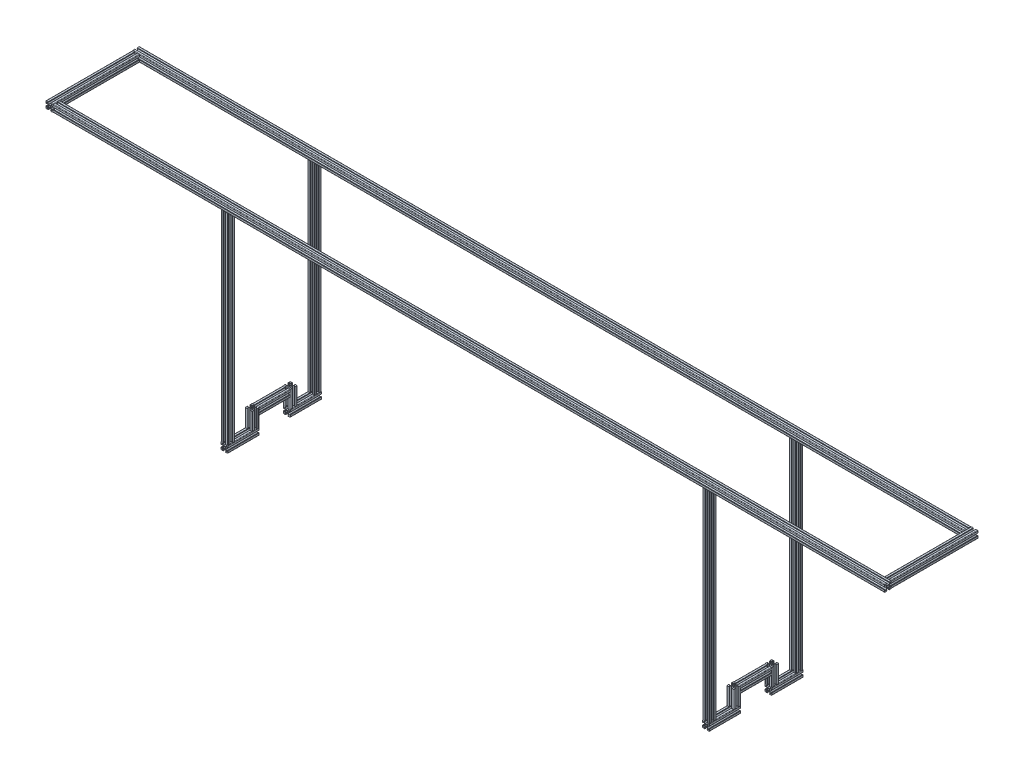
SolidWorks part; units mm, degrees
ref_plane "前视基准面" through (0, 0, 0) normal (0, 0, 1) x (1, 0, 0)
ref_plane "上视基准面" through (0, 0, 0) normal (0, 1, 0) x (1, 0, 0)
ref_plane "右视基准面" through (0, 0, 0) normal (1, 0, 0) x (0, 0, -1)
sketch "草图3" plane through (0, 0, 0) normal (0, 1, 0) x (1, 0, 0)
  line L0 (0, 0) -> (0, 250)
  line L1 (0, 250) -> (2400, 250)
  line L2 (2400, 250) -> (2400, 0)
  line L3 (2400, 0) -> (0, 0)
  dimension "D1" = 2400
  dimension "D2" = 250
sketch3d "3D草图2"
  line L0 (1200, 600, 0) -> (1200, -51.0391, 0) construction
  line L1 (2400, 0, -250) -> (2400, 0, 0) construction
  line L2 (505, 600, 0) -> (505, 0, 0)
  line L3 (0, 0, 0) -> (0, 0, -250) construction
  line L5 (2400, 0, -250) -> (2400, 0, 0) construction
  line L7 (0, 0, 0) -> (0, 0, -250) construction
  line L9 (0, 600, 0) -> (0, 600, -250)
  line L10 (0, 600, -250) -> (0, 0, -250) construction
  line L11 (0, 600, 0) -> (2400, 600, 0)
  line L12 (2400, 600, 0) -> (2400, 0, 0) construction
  line L13 (2400, 600, 0) -> (2400, 600, -250)
  line L14 (2400, 600, -250) -> (2400, 0, -250) construction
  line L15 (0, 600, -250) -> (2400, 600, -250)
  line L16 (1895, 600, 0) -> (1895, 0, 0)
  line L17 (1895, 600, -250) -> (1895, 0, -250)
  line L18 (505, 600, -250) -> (505, 0, -250)
  line L19 (1200, 600, -250) -> (1200, -43.6003, -250) construction
  line L20 (505, 0, 0) -> (505, 0, -70)
  line L21 (1895, 0, 0) -> (1895, 0, -70)
  line L22 (505, 0, -180) -> (505, 50, -180)
  line L23 (505, 50, -180) -> (505, 50, -70)
  line L24 (505, 50, -70) -> (505, 0, -70)
  line L25 (505, 0, -180) -> (505, 0, -250)
  line L26 (1895, 0, -70) -> (1895, 50, -70)
  line L27 (1895, 50, -70) -> (1895, 50, -180)
  line L28 (1895, 50, -180) -> (1895, 0, -180)
  line L29 (1895, 0, -180) -> (1895, 0, -250)
  dimension "D1" = 600
  dimension "D2" = 600
  dimension "D7" = 600
  dimension "D3" = 695
  dimension "D4" = 600
  dimension "D5" = 695
  dimension "D6" = 695
  dimension "D8" = 695
  dimension "D9" = 600
  dimension "D10" = 110
  dimension "D11" = 50
  dimension "D12" = 70
  dimension "D13" = 70
  dimension "D14" = 110
  dimension "D15" = 50
  dimension "D16" = 70
  dimension "D17" = 70
other "工业铝型材 20 X 20 X R1.5(1)"
ref_plane "基准面2" through (0, 600, 0) normal (0, 0, -1) x (1, 0, 0)
sketch "Sketch14" plane through (0, 600, 0) normal (0, 0, -1) x (1, 0, 0)
  line L0 (-3.6, 10) -> (-3.6, 9.5)
  line L1 (-3.6, 9.5) -> (-3.1, 9.5)
  line L2 (-3.1, 9.5) -> (-3.1, 8.5)
  line L3 (-3.1, 8.5) -> (-5.5, 8.5)
  line L4 (-8.5, -10) -> (-3.6, -10)
  line L5 (-10, -8.5) -> (-10, -3.6)
  line L6 (8.5, 10) -> (3.6, 10)
  line L7 (10, 8.5) -> (10, 3.6)
  line L8 (0, 14.8756) -> (0, 0) construction
  line L9 (0, 0) -> (14.1675, 0) construction
  line L10 (-5.5, 8.5) -> (-5.5, 6.65)
  line L11 (-5.5, 6.65) -> (-2.75, 3.9)
  line L12 (-2.75, 3.9) -> (2.75, 3.9)
  line L13 (5.5, 6.65) -> (2.75, 3.9)
  line L14 (5.5, 8.5) -> (5.5, 6.65)
  line L15 (3.1, 8.5) -> (5.5, 8.5)
  line L16 (3.1, 9.5) -> (3.1, 8.5)
  line L17 (3.6, 9.5) -> (3.1, 9.5)
  line L18 (3.6, 10) -> (3.6, 9.5)
  line L19 (-3.6, 10) -> (-8.5, 10)
  line L20 (10, 3.6) -> (9.5, 3.6)
  line L21 (9.5, 3.6) -> (9.5, 3.1)
  line L22 (9.5, 3.1) -> (8.5, 3.1)
  line L23 (8.5, 3.1) -> (8.5, 5.5)
  line L24 (8.5, 5.5) -> (6.65, 5.5)
  line L25 (6.65, 5.5) -> (3.9, 2.75)
  line L26 (3.9, 2.75) -> (3.9, -2.75)
  line L27 (6.65, -5.5) -> (3.9, -2.75)
  line L28 (8.5, -5.5) -> (6.65, -5.5)
  line L29 (8.5, -3.1) -> (8.5, -5.5)
  line L30 (9.5, -3.1) -> (8.5, -3.1)
  line L31 (9.5, -3.6) -> (9.5, -3.1)
  line L32 (10, -3.6) -> (9.5, -3.6)
  line L33 (3.6, -10) -> (3.6, -9.5)
  line L34 (3.6, -9.5) -> (3.1, -9.5)
  line L35 (3.1, -9.5) -> (3.1, -8.5)
  line L36 (3.1, -8.5) -> (5.5, -8.5)
  line L37 (5.5, -8.5) -> (5.5, -6.65)
  line L38 (5.5, -6.65) -> (2.75, -3.9)
  line L39 (2.75, -3.9) -> (-2.75, -3.9)
  line L40 (-5.5, -6.65) -> (-2.75, -3.9)
  line L41 (-5.5, -8.5) -> (-5.5, -6.65)
  line L42 (-3.1, -8.5) -> (-5.5, -8.5)
  line L43 (-3.1, -9.5) -> (-3.1, -8.5)
  line L44 (-3.6, -9.5) -> (-3.1, -9.5)
  line L45 (-3.6, -10) -> (-3.6, -9.5)
  line L46 (-10, -3.6) -> (-9.5, -3.6)
  line L47 (-9.5, -3.6) -> (-9.5, -3.1)
  line L48 (-9.5, -3.1) -> (-8.5, -3.1)
  line L49 (-8.5, -3.1) -> (-8.5, -5.5)
  line L50 (-8.5, -5.5) -> (-6.65, -5.5)
  line L51 (-6.65, -5.5) -> (-3.9, -2.75)
  line L52 (-3.9, -2.75) -> (-3.9, 2.75)
  line L53 (-6.65, 5.5) -> (-3.9, 2.75)
  line L54 (-8.5, 5.5) -> (-6.65, 5.5)
  line L55 (-8.5, 3.1) -> (-8.5, 5.5)
  line L56 (-9.5, 3.1) -> (-8.5, 3.1)
  line L57 (-9.5, 3.6) -> (-9.5, 3.1)
  line L58 (-10, 3.6) -> (-9.5, 3.6)
  line L59 (3.6, -10) -> (8.5, -10)
  line L60 (-10, 3.6) -> (-10, 8.5)
  line L61 (10, -3.6) -> (10, -8.5)
  circle A0 centre (0, 0) radius 2.5
  arc A1 (-10, 8.5) -> (-8.5, 10) centre (-8.5, 8.5) cw
  arc A2 (10, 8.5) -> (8.5, 10) centre (8.5, 8.5) ccw
  arc A3 (-8.5, -10) -> (-10, -8.5) centre (-8.5, -8.5) cw
  arc A4 (8.5, -10) -> (10, -8.5) centre (8.5, -8.5) ccw
  point P0 (-10, 0)
  point P1 (10, 0)
  point P2 (0, 10)
  point P3 (0, -10)
  point P4 (0, 0)
  point P5 (-10, -10)
  point P6 (10, -10)
  point P7 (10, 10)
  point P8 (-10, 10)
  point P13 (0, 0)
  point P36 (-10, 10)
  point P39 (10, 10)
  point P43 (0, 0)
  point P44 (0, 0)
  dimension "D1" = 11
  dimension "D2" = 20
  dimension "D3" = 6.2
  dimension "D4" = 7.2
  dimension "D5" = 6.1
  dimension "D6" = 5
  dimension "D7" = 1.5
  dimension "D8" = 45
  dimension "D9" = 0.5
  dimension "D10" = 1
  dimension "D11" = 5.5
